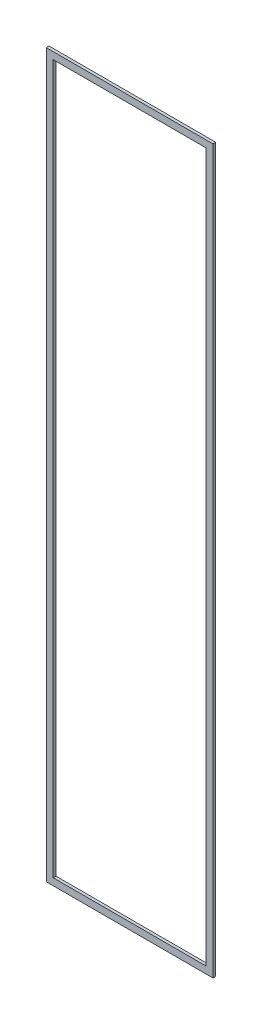
SolidWorks part; units mm, degrees
ref_plane "Front Plane" through (0, 0, 0) normal (0, 0, 1) x (1, 0, 0)
ref_plane "Top Plane" through (0, 0, 0) normal (0, 1, 0) x (1, 0, 0)
ref_plane "Right Plane" through (0, 0, 0) normal (1, 0, 0) x (0, 0, -1)
sketch "Sketch1" plane through (0, 0, 0) normal (0, 0, 1) x (1, 0, 0)
  line L1 (300, -1300) -> (-300, -1300)
  line L2 (300, -1300) -> (300, 1300)
  line L3 (300, 1300) -> (-300, 1300)
  line L4 (-300, -1300) -> (-300, 1300)
  line L5 (300, -1300) -> (-300, 1300) construction
  line L6 (300, 1300) -> (-300, -1300) construction
  line L7 (275, -1275) -> (-275, -1275)
  line L8 (275, -1275) -> (275, 1275)
  line L9 (275, 1275) -> (-275, 1275)
  line L10 (-275, -1275) -> (-275, 1275)
  line L11 (275, -1275) -> (-275, 1275) construction
  line L12 (275, 1275) -> (-275, -1275) construction
  point P0 (0, 0)
  point P6 (0, 0)
extrude "Boss-Extrude1" add sketch "Sketch1" along normal blind 10
